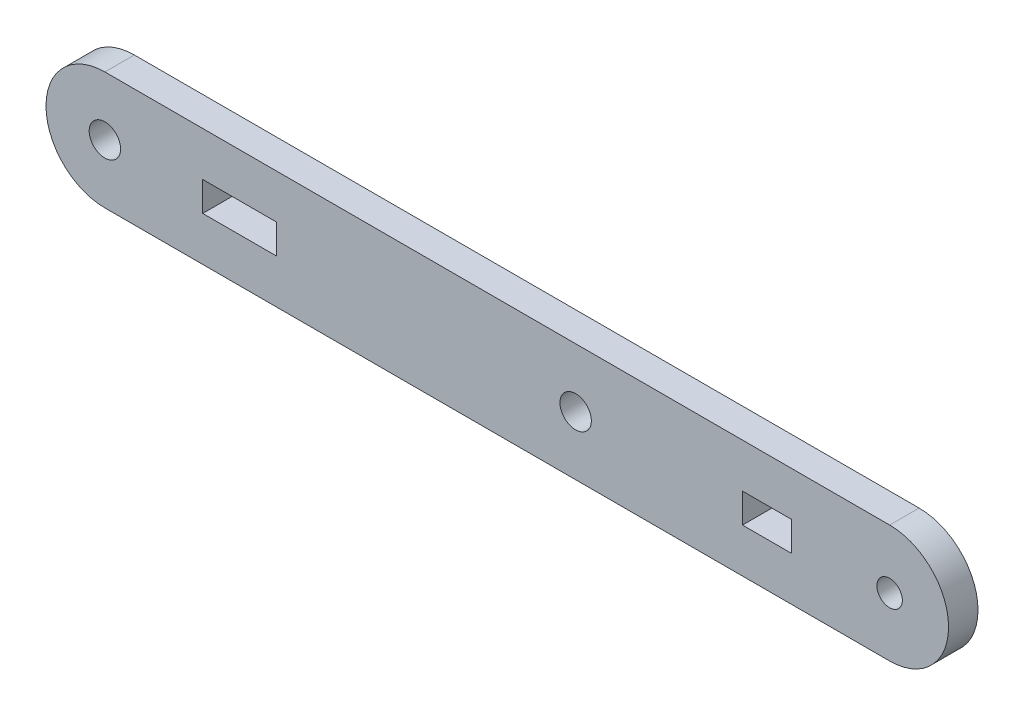
SolidWorks part; units mm, degrees
ref_plane "前视基准面" through (0, 0, 0) normal (0, 0, 1) x (1, 0, 0)
ref_plane "上视基准面" through (0, 0, 0) normal (0, 1, 0) x (1, 0, 0)
ref_plane "右视基准面" through (0, 0, 0) normal (1, 0, 0) x (0, 0, -1)
ref_plane "基准面4" through (0, 0, 0) normal (0, 0, -1) x (-1, 0, 0)
sketch "草图1" plane through (0, 0, 0) normal (0, 0, -1) x (-1, 0, 0)
  line L0 (39.3783, 4.4994) -> (31.8791, 4.4994)
  line L1 (31.8791, 4.4994) -> (31.8791, 7.4995)
  line L2 (31.8791, 7.4995) -> (39.3783, 7.4995)
  line L3 (39.3783, 7.4995) -> (39.3783, 4.4994)
  line L4 (-30.6182, 0) -> (49.3435, 0)
  line L5 (49.3435, 12) -> (-30.6182, 12)
  line L6 (-15.6218, 7.4995) -> (-15.6218, 4.4994)
  line L7 (-15.6218, 4.4994) -> (-20.6213, 4.4994)
  line L8 (-20.6213, 4.4994) -> (-20.6213, 7.4995)
  line L9 (-20.6213, 7.4995) -> (-15.6218, 7.4995)
  arc A0 (49.3435, 0) -> (49.3435, 12) centre (49.3435, 6) ccw
  arc A1 (-30.6182, 12) -> (-30.6182, 0) centre (-30.6182, 6) ccw
  circle A2 centre (49.3435, 6) radius 1.3
  circle A3 centre (1.3793, 6.0002) radius 1.3
  circle A4 centre (-30.6116, 6.0001) radius 1.3
extrude "凸台-拉伸1" add sketch "草图1" against normal blind 3
sketch "草图2" plane through (0, 0, 3) normal (0, 0, 1) x (1, 0, 0)
  circle A0 centre (-49.3435, 6) radius 1.6
  circle A1 centre (-1.3793, 6.0002) radius 1.6
  dimension "D1" = 3.2
extrude "切除-拉伸1" cut sketch "草图2" against normal through all
